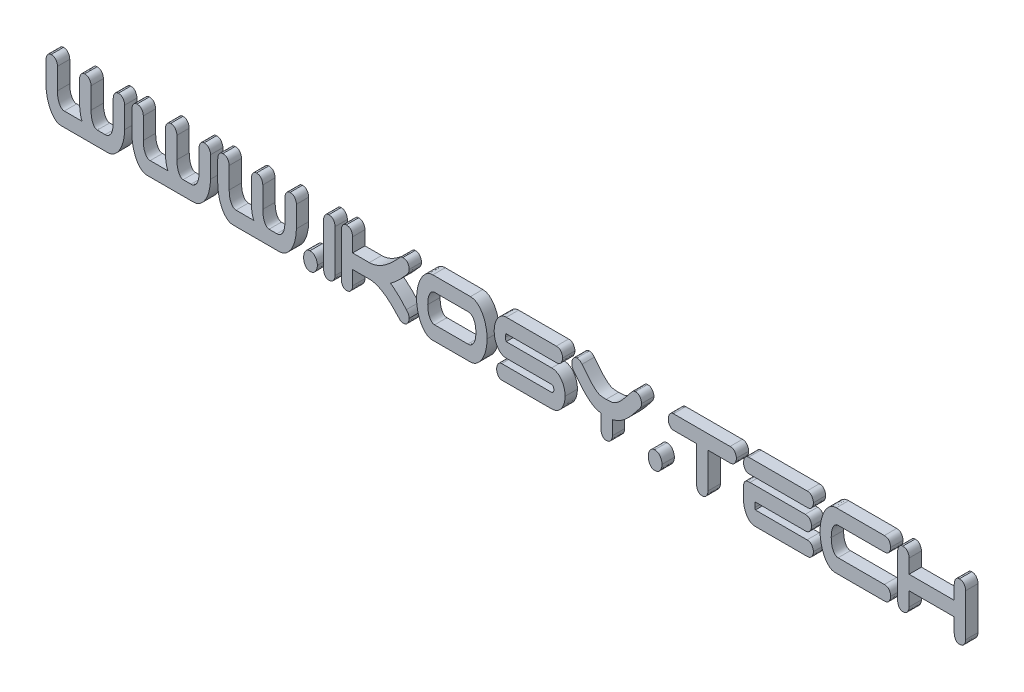
SolidWorks part; units mm, degrees
other "Text Extrude - I"
other "Text Extrude - ."
other "Text Extrude - W3"
other "Text Extrude - W2"
other "Text Extrude - W1" parameters "D1"=19.4587, "D2"=1.1925, "D3"=36.394, "D4"=188.1767, "D5"=2.5
ref_plane "Front Plane" through (0, 0, 0) normal (0, 0, 1) x (1, 0, 0)
ref_plane "Top Plane" through (0, 0, 0) normal (0, 1, 0) x (1, 0, 0)
ref_plane "Right Plane" through (0, 0, 0) normal (1, 0, 0) x (0, 0, -1)
sketch "Insertion Point Sketch" plane through (0, 0, 0) normal (0, 0, 1) x (1, 0, 0)
  line L0 (-2.5, -2.5) -> (-2.5, 0) construction
  line L1 (-2.5, -2.5) -> (0, -2.5) construction
  dimension "D1" = 2.5
  dimension "D2" = 2.5
ref_plane "3D Printing Base Plane" through (0, 0, -4) normal (0, 0, 1) x (1, 0, 0)
sketch "3D Printing Origin Sketch" plane through (0, 0, -4) normal (0, 0, 1) x (1, 0, 0)
  point P0 (-23.75, -5)
  point P1 (0, 0)
  point P2 (0, 0)
  point P4 (0, 0)
  point P5 (-31.7966, -16.824)
  dimension "D1" = 2.5
  dimension "D2" = 21.25
sketch "Text Sketch" plane through (0, 0, 0) normal (0, 0, 1) x (1, 0, 0)
  line L0 (-5, 15) -> (187.5, 15) construction
  line L1 (187.5, 15) -> (187.5, -5) construction
  line L2 (187.5, -5) -> (-5, -5) construction
  line L3 (187.5, 12.5) -> (-2.5, 12.5) construction
  line L4 (187.5, -2.5) -> (-2.5, -2.5) construction
  line L5 (-5, 15) -> (-5, -5) construction
  line L6 (-2.5, -2.5) -> (-2.5, 12.5) construction
  text T0 "www.ikosy.tech" font "Space Age" height 11.5
  point P3 (0, 0)
  point P7 (0, 0)
  point P8 (15.2253, 11.1843)
  point P9 (0, 0)
  dimension "D1" = 2.5
  dimension "D4" = 187.5
  dimension "D3" = 2.5
  dimension "D2" = 20
extrude "Text Extrude" add sketch "Text Sketch" along normal blind 2.5 separate body
equation "\"Logo Height\"= \"Total Height\" - 2 * \"Border\""
equation "\"Total Height\"= 20"
equation "\"Border\" = 2.5"
equation "\"D1@Insertion Point Sketch\" = \"Border\""
equation "\"D2@Insertion Point Sketch\" = \"Border\""
equation "\"D2@Text Sketch\"=\"Total Height\""
equation "\"D5@Text Sketch\"=\"Border\""
equation "\"D3@Text Sketch\"=\"Border\""
equation "\"D1@Text Sketch\"=\"Border\""
equation "\"D1@3D Printing Origin Sketch\"=\"Border\""
